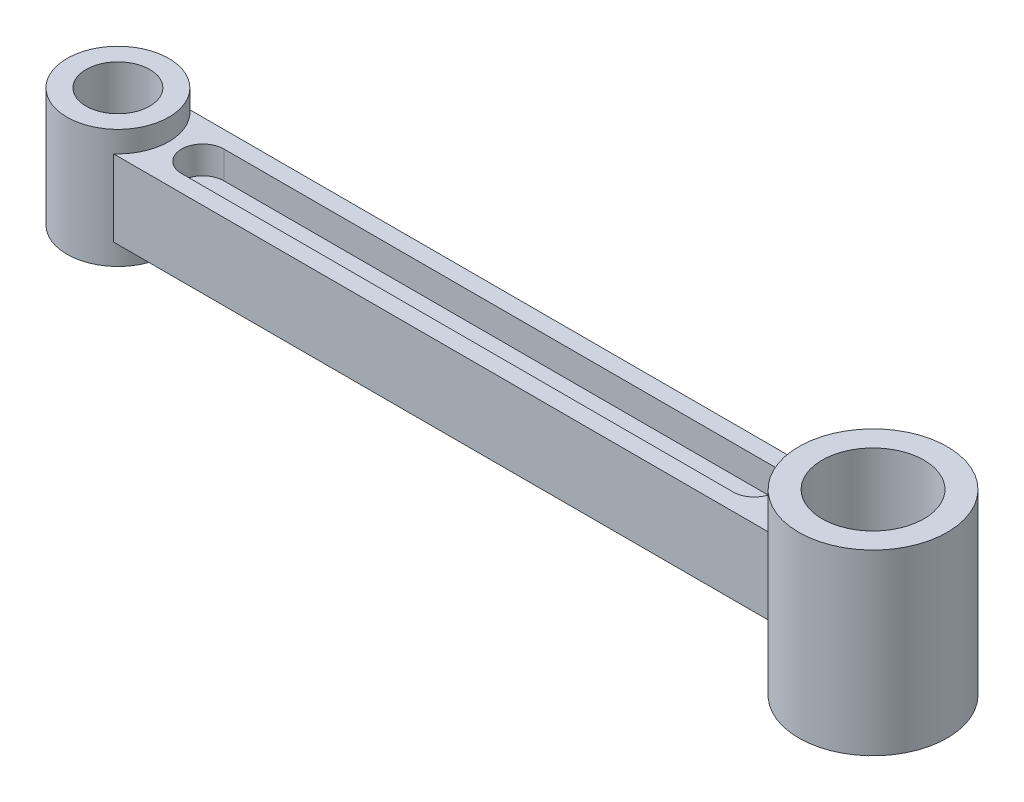
SolidWorks part; units mm, degrees
ref_plane "Front Plane" through (0, 0, 0) normal (0, 0, 1) x (1, 0, 0)
ref_plane "Top Plane" through (0, 0, 0) normal (0, 1, 0) x (1, 0, 0)
ref_plane "Right Plane" through (0, 0, 0) normal (1, 0, 0) x (0, 0, -1)
sketch "Sketch1" plane through (0, 0, 0) normal (0, 1, 0) x (1, 0, 0)
  circle A2 centre (-108.997, 0) radius 7.5
  circle A3 centre (-108.997, 0) radius 12
  point P4 (0, 0)
  point P21 (0, 0)
  dimension "D3" = 15
  dimension "D4" = 24
extrude "Boss-Extrude2" add sketch "Sketch1" along normal mid plane 28
sketch "Sketch6" plane through (0, 0, 0) normal (0, 1, 0) x (1, 0, 0)
  line L0 (-108.997, 0) -> (69.003, 0) construction
  circle A0 centre (-108.997, 0) radius 7.5 construction
  circle A1 centre (69.003, 0) radius 17.5
  circle A2 centre (69.003, 0) radius 12
  dimension "D1" = 35
  dimension "D2" = 24
  dimension "D3" = 178
extrude "Boss-Extrude6" add sketch "Sketch6" along normal mid plane 42 separate body
sketch "Sketch10" plane through (0, 0, 0) normal (0, 1, 0) x (1, 0, 0)
  line L0 (-108.997, 0) -> (69.003, 0) construction
  line L1 (53.9947, 9) -> (-101.0597, 9)
  line L2 (53.9947, -9) -> (-101.0597, -9)
  circle A0 centre (69.003, 0) radius 17.5 construction
  circle A1 centre (-108.997, 0) radius 12 construction
  arc A2 (-101.0597, 9) -> (-101.0597, -9) centre (-108.997, 0) cw
  arc A3 (53.9947, -9) -> (53.9947, 9) centre (69.003, 0) cw
  dimension "D1" = 9
extrude "Boss-Extrude7" add sketch "Sketch10" along normal mid plane 18
sketch "Sketch11" plane through (0, 9, 0) normal (0, 1, 0) x (1, 0, 0)
  line L2 (-88.997, 5) -> (41.003, 5)
  line L3 (41.003, -5) -> (-88.997, -5)
  arc A0 (-88.997, 5) -> (-88.997, -5) centre (-88.997, 0) ccw
  arc A1 (41.003, -5) -> (41.003, 5) centre (41.003, 0) ccw
  circle A2 centre (-108.997, 0) radius 7.5 construction
  circle A3 centre (69.003, 0) radius 12 construction
  dimension "D1" = 5
  dimension "D3" = 5
  dimension "D4" = 20
  dimension "D2" = 130
  dimension "D5" = 28
extrude "Cut-Extrude1" cut sketch "Sketch11" against normal blind 6.5
mirror "Mirror1" about plane through (0, 0, 0) normal (0, 1, 0) of "Cut-Extrude1"
